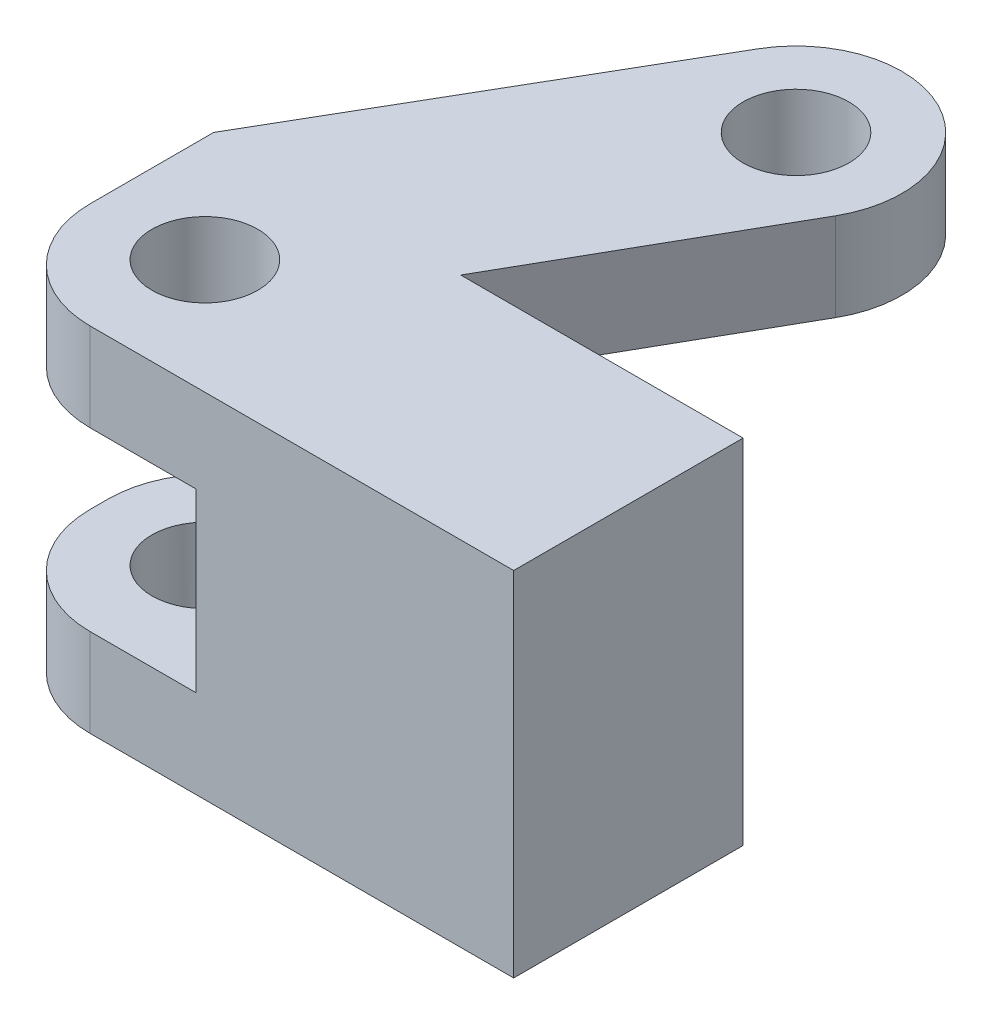
SolidWorks part; units mm, degrees
ref_plane "前视基准面" through (0, 0, 0) normal (0, 0, 1) x (1, 0, 0)
ref_plane "上视基准面" through (0, 0, 0) normal (0, 1, 0) x (1, 0, 0)
ref_plane "右视基准面" through (0, 0, 0) normal (1, 0, 0) x (0, 0, -1)
sketch "草图1" plane through (0, 0, 0) normal (0, 1, 0) x (1, 0, 0)
  line L1 (-15, 6.5) -> (15, 6.5)
  line L2 (-15, 6.5) -> (-15, -6.5)
  line L3 (-15, -6.5) -> (15, -6.5)
  line L4 (15, 6.5) -> (15, -6.5)
  line L5 (-15, 6.5) -> (15, -6.5) construction
  line L6 (-15, -6.5) -> (15, 6.5) construction
  point P0 (0, 0)
  dimension "D1" = 13
  dimension "D2" = 30
extrude "凸台-拉伸1" add sketch "草图1" along normal mid plane 20
sketch "草图2" plane through (0, 0, -6.5) normal (0, 0, -1) x (-1, 0, 0)
  line L0 (15, 10) -> (15, -10) construction
  line L1 (27, -5) -> (3, -5)
  line L2 (27, -5) -> (27, 5)
  line L3 (27, 5) -> (3, 5)
  line L4 (3, -5) -> (3, 5)
  line L5 (27, -5) -> (3, 5) construction
  line L6 (27, 5) -> (3, -5) construction
  line L7 (-15, -10) -> (15, -10) construction
  point P0 (15, 0)
  dimension "D1" = 10
  dimension "D2" = 5
  dimension "D3" = 12
extrude "切除-拉伸1" cut sketch "草图2" against normal blind 20
sketch "草图3" plane through (0, 10, 0) normal (0, 1, 0) x (1, 0, 0)
  line L0 (-3.6909, 26.0091) -> (-15, 6.5)
  line L1 (-15, 6.5) -> (-1, 6.5)
  line L2 (15, 6.5) -> (-15, 6.5) construction
  line L3 (-1, 6.5) -> (6.7125, 20.0284)
  line L4 (-15, 6.5) -> (-15, -6.5) construction
  circle A0 centre (1.5, 23) radius 3
  arc A1 (6.7125, 20.0284) -> (-3.6909, 26.0091) centre (1.5, 23) ccw
  dimension "D1" = 6
  dimension "D2" = 12
  dimension "D3" = 16.5
  dimension "D5" = 16.5
  dimension "D4" = 14
extrude "凸台-拉伸2" add sketch "草图3" against normal blind 5
sketch "草图4" plane through (0, 10, 0) normal (0, 1, 0) x (1, 0, 0)
  line L0 (-15, 6.5) -> (-15, -6.5) construction
  line L1 (-15, -6.5) -> (15, -6.5) construction
  circle A0 centre (-9, 0) radius 3
  dimension "D1" = 6
  dimension "D2" = 6
  dimension "D3" = 6.5
extrude "切除-拉伸2" cut sketch "草图4" against normal through all
fillet "圆角1" radius 6 3 edges at (-15, 7.5, 6.5) (-15, -7.5, 6.5) (-15, -7.5, -6.5)
